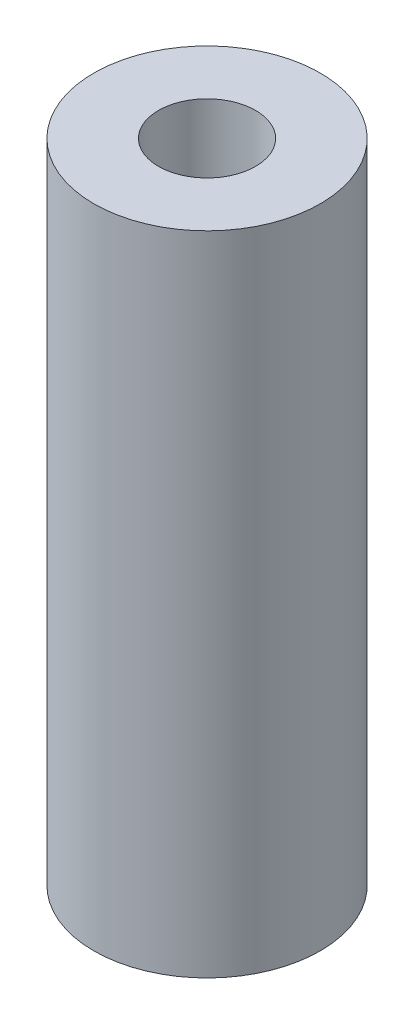
SolidWorks part; units mm, degrees
ref_plane "前视基准面" through (0, 0, 0) normal (0, 0, 1) x (1, 0, 0)
ref_plane "上视基准面" through (0, 0, 0) normal (0, 1, 0) x (1, 0, 0)
ref_plane "右视基准面" through (0, 0, 0) normal (1, 0, 0) x (0, 0, -1)
sketch "草图1" plane through (0, 0, 0) normal (0, 1, 0) x (1, 0, 0)
  circle A0 centre (0, 0) radius 1.5
  circle A1 centre (0, 0) radius 3.5
extrude "凸台-拉伸2" add sketch "草图1" along normal blind 20
